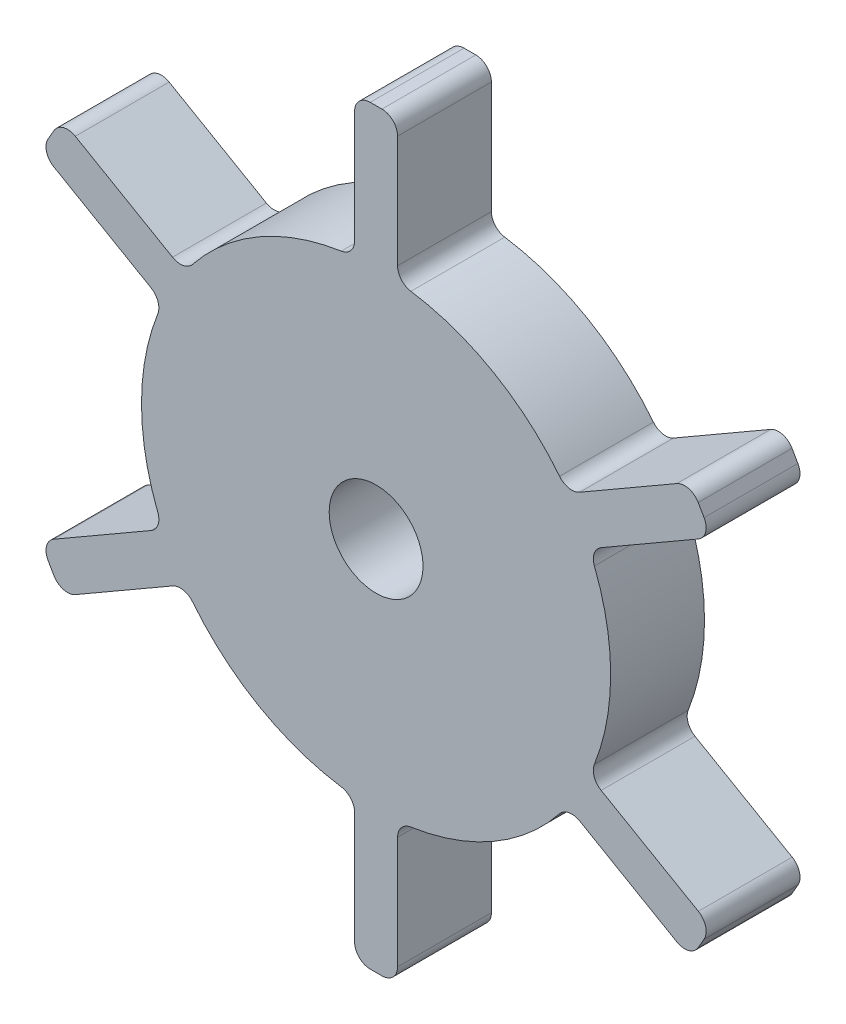
SolidWorks part; units mm, degrees
ref_plane "Front Plane" through (0, 0, 0) normal (0, 0, 1) x (1, 0, 0)
ref_plane "Top Plane" through (0, 0, 0) normal (0, 1, 0) x (1, 0, 0)
ref_plane "Right Plane" through (0, 0, 0) normal (1, 0, 0) x (0, 0, -1)
sketch "Sketch1" plane through (0, 0, 0) normal (0, 0, 1) x (1, 0, 0)
  circle A0 centre (0, 0) radius 76.2
  circle A1 centre (0, 0) radius 381
  dimension "D1" = 152.4
  dimension "D2" = 304.8
extrude "Boss-Extrude1" add sketch "Sketch1" along normal mid plane 152.4
sketch "Sketch2" plane through (0, 0, 76.2) normal (0, 0, 1) x (1, 0, 0)
  line L0 (-34.925, 379.3959) -> (-34.925, 609.6)
  line L1 (-34.925, 609.6) -> (34.925, 609.6)
  line L2 (34.925, 609.6) -> (34.925, 379.3959)
  line L3 (0, 0) -> (0, 1219.2) construction
  circle A0 centre (0, 0) radius 381 construction
  arc A1 (34.925, 379.3959) -> (-34.925, 379.3959) centre (0, 0) ccw
  point P9 (0, 609.6)
  dimension "D1" = 69.85
  dimension "D2" = 609.6
extrude "Boss-Extrude2" add sketch "Sketch2" against normal up to surface (152.4 mm away) up to face at (381, 0, -76.2)
fillet "Fillet1" radius 25.4 4 edges at (-34.925, 379.3959, 0) (-34.925, 609.6, 0) (34.925, 609.6, 0) (34.925, 379.3959, 0)
pattern_circular "CirPattern1" count 6 over 360 about axis through (0, 0, 0) along (0, 0, 1) of "Boss-Extrude2", "Fillet1"
